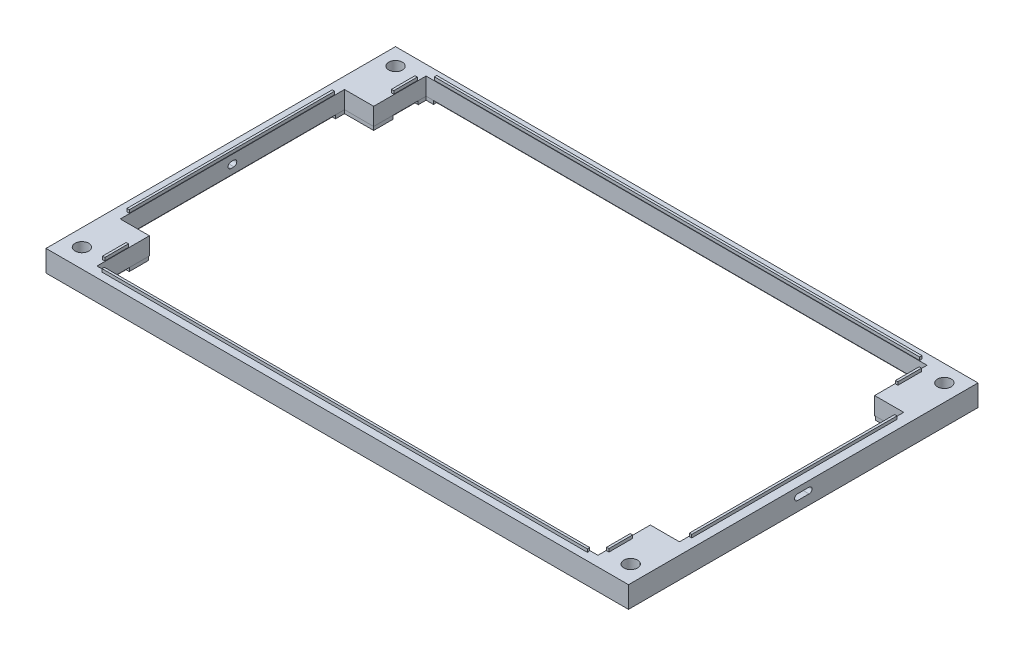
SolidWorks part; units mm, degrees
ref_plane "Front Plane" through (0, 0, 0) normal (0, 0, 1) x (1, 0, 0)
ref_plane "Top Plane" through (0, 0, 0) normal (0, 1, 0) x (1, 0, 0)
ref_plane "Right Plane" through (0, 0, 0) normal (1, 0, 0) x (0, 0, -1)
sketch "Sketch1" plane through (0, 0, 0) normal (0, 1, 0) x (1, 0, 0)
  line L0 (38.5216, 77.8504) -> (222.6228, 77.8504) construction
  line L1 (14, 116.5) -> (186, 116.5) construction
  line L2 (0, 120) -> (200, 120)
  line L3 (0, 120) -> (0, 0)
  line L4 (0, 0) -> (200, 0)
  line L5 (200, 120) -> (200, 0)
  line L6 (186, 116.5) -> (186, 98.5) construction
  line L7 (186, 98.5) -> (196, 98.5) construction
  line L8 (196, 98.5) -> (196, 21.5) construction
  line L9 (196, 21.5) -> (186, 21.5) construction
  line L10 (186, 21.5) -> (186, 3.5) construction
  line L11 (186, 3.5) -> (14, 3.5) construction
  line L12 (14, 3.5) -> (14, 21.5) construction
  line L13 (14, 21.5) -> (4, 21.5) construction
  line L14 (4, 21.5) -> (4, 98.5) construction
  line L15 (4, 98.5) -> (14, 98.5) construction
  line L16 (14, 98.5) -> (14, 116.5) construction
  line L17 (0, 60) -> (200, 60) construction
  line L18 (100, 120) -> (100, 0) construction
  line L19 (4, 60) -> (196, 60) construction
  line L20 (100, 116.5) -> (100, 3.5) construction
  line L21 (2.9, 20.4) -> (2.9, 99.6) construction
  line L22 (5.8062, 114.2159) -> (194.233, 114.2159) construction
  line L23 (5.8062, 114.2159) -> (5.8062, 6.516) construction
  line L24 (5.8062, 6.516) -> (194.233, 6.516) construction
  line L25 (194.233, 114.2159) -> (194.233, 6.516) construction
  line L26 (2.9, 99.6) -> (12.9, 99.6) construction
  line L27 (12.9, 99.6) -> (12.9, 117.6) construction
  line L28 (12.9, 117.6) -> (187.1, 117.6) construction
  line L29 (187.1, 117.6) -> (187.1, 99.6) construction
  line L30 (187.1, 99.6) -> (197.1, 99.6) construction
  line L31 (197.1, 99.6) -> (197.1, 20.4) construction
  line L32 (197.1, 20.4) -> (187.1, 20.4) construction
  line L33 (187.1, 20.4) -> (187.1, 2.4) construction
  line L34 (187.1, 2.4) -> (12.9, 2.4) construction
  line L35 (12.9, 2.4) -> (12.9, 20.4) construction
  line L36 (12.9, 20.4) -> (2.9, 20.4) construction
  line L85 (2.9, 95.4076) -> (4, 95.4076)
  line L86 (12.9, 105.4022) -> (14, 105.4022)
  line L87 (12.9, 113.8056) -> (14, 113.8056)
  line L88 (16.5433, 116.5) -> (16.5433, 117.6)
  line L89 (197.1, 95.4076) -> (196, 95.4076)
  line L90 (187.1, 105.4022) -> (186, 105.4022)
  line L91 (187.1, 113.8056) -> (186, 113.8056)
  line L92 (183.4567, 116.5) -> (183.4567, 117.6)
  line L93 (197.1, 24.5924) -> (196, 24.5924)
  line L94 (187.1, 14.5978) -> (186, 14.5978)
  line L95 (187.1, 6.1944) -> (186, 6.1944)
  line L96 (183.4567, 3.5) -> (183.4567, 2.4)
  line L97 (16.5433, 3.5) -> (16.5433, 2.4)
  line L98 (12.9, 6.1944) -> (14, 6.1944)
  line L99 (12.9, 14.5978) -> (14, 14.5978)
  line L100 (2.9, 24.5924) -> (4, 24.5924)
  line L101 (2.9, 95.4076) -> (2.9, 24.5924)
  line L102 (4, 24.5924) -> (4, 95.4076)
  line L103 (12.9, 14.5978) -> (12.9, 6.1944)
  line L104 (14, 6.1944) -> (14, 14.5978)
  line L105 (16.5433, 3.5) -> (183.4567, 3.5)
  line L106 (183.4567, 2.4) -> (16.5433, 2.4)
  line L107 (186, 6.1944) -> (186, 14.5978)
  line L108 (187.1, 14.5978) -> (187.1, 6.1944)
  line L109 (196, 24.5924) -> (196, 95.4076)
  line L110 (197.1, 95.4076) -> (197.1, 24.5924)
  line L111 (187.1, 105.4022) -> (187.1, 113.8056)
  line L112 (186, 113.8056) -> (186, 105.4022)
  line L113 (183.4567, 117.6) -> (16.5433, 117.6)
  line L114 (16.5433, 116.5) -> (183.4567, 116.5)
  line L115 (12.9, 105.4022) -> (12.9, 113.8056)
  line L116 (14, 113.8056) -> (14, 105.4022)
  line L117 (4, 95.4076) -> (4, 98.5)
  line L118 (4, 98.5) -> (14, 98.5)
  line L119 (14, 98.5) -> (14, 105.4022)
  line L120 (183.4567, 116.5) -> (186, 116.5)
  line L121 (186, 116.5) -> (186, 113.8056)
  line L122 (186, 105.4022) -> (186, 98.5)
  line L123 (186, 98.5) -> (196, 98.5)
  line L124 (196, 98.5) -> (196, 95.4076)
  line L125 (196, 24.5924) -> (196, 21.5)
  line L126 (196, 21.5) -> (186, 21.5)
  line L127 (186, 21.5) -> (186, 14.5978)
  line L128 (186, 6.1944) -> (186, 3.5)
  line L129 (186, 3.5) -> (183.4567, 3.5)
  line L130 (16.5433, 3.5) -> (14, 3.5)
  line L131 (14, 3.5) -> (14, 6.1944)
  line L132 (14, 14.5978) -> (14, 21.5)
  line L133 (14, 21.5) -> (4, 21.5)
  line L134 (4, 21.5) -> (4, 24.5924)
  line L135 (14, 113.8056) -> (14, 116.5)
  line L136 (14, 116.5) -> (16.5433, 116.5)
  circle A0 centre (5.8062, 114.2159) radius 2.35
  circle A1 centre (194.233, 114.2159) radius 2.35
  circle A2 centre (194.233, 6.516) radius 2.35
  circle A3 centre (5.8062, 6.516) radius 2.35
  dimension "D7" = 4.7
  dimension "D1" = 120
  dimension "D2" = 200
  dimension "D3" = 113
  dimension "D4" = 192
  dimension "D5" = 172
  dimension "D6" = 77
  dimension "D8" = 1.1
sketch "Sketch8" plane through (0, 0, 0) normal (0, 1, 0) x (1, 0, 0)
  line L0 (2.9, 24.5924) -> (4, 24.5924) construction
  line L1 (4, 21.5) -> (4, 24.5924) construction
  line L2 (14, 21.5) -> (4, 21.5) construction
  line L3 (14, 14.5978) -> (14, 21.5) construction
  line L4 (12.9, 14.5978) -> (14, 14.5978) construction
  line L5 (12.9, 14.5978) -> (12.9, 6.1944) construction
  line L6 (12.9, 6.1944) -> (14, 6.1944) construction
  line L7 (14, 3.5) -> (14, 6.1944) construction
  line L8 (16.5433, 3.5) -> (14, 3.5) construction
  line L9 (16.5433, 3.5) -> (16.5433, 2.4) construction
  line L10 (183.4567, 2.4) -> (16.5433, 2.4) construction
  line L11 (183.4567, 3.5) -> (183.4567, 2.4) construction
  line L12 (186, 3.5) -> (183.4567, 3.5) construction
  line L13 (186, 6.1944) -> (186, 3.5) construction
  line L14 (187.1, 6.1944) -> (186, 6.1944) construction
  line L15 (187.1, 14.5978) -> (187.1, 6.1944) construction
  line L16 (187.1, 14.5978) -> (186, 14.5978) construction
  line L17 (186, 21.5) -> (186, 14.5978) construction
  line L18 (196, 21.5) -> (186, 21.5) construction
  line L19 (196, 24.5924) -> (196, 21.5) construction
  line L20 (197.1, 24.5924) -> (196, 24.5924) construction
  line L21 (197.1, 95.4076) -> (197.1, 24.5924) construction
  line L22 (197.1, 95.4076) -> (196, 95.4076) construction
  line L23 (196, 98.5) -> (196, 95.4076) construction
  line L24 (186, 98.5) -> (196, 98.5) construction
  line L25 (186, 105.4022) -> (186, 98.5) construction
  line L26 (187.1, 105.4022) -> (186, 105.4022) construction
  line L27 (187.1, 105.4022) -> (187.1, 113.8056) construction
  line L28 (187.1, 113.8056) -> (186, 113.8056) construction
  line L29 (186, 116.5) -> (186, 113.8056) construction
  line L30 (183.4567, 116.5) -> (186, 116.5) construction
  line L31 (183.4567, 116.5) -> (183.4567, 117.6) construction
  line L32 (183.4567, 117.6) -> (16.5433, 117.6) construction
  line L33 (16.5433, 116.5) -> (16.5433, 117.6) construction
  line L34 (14, 116.5) -> (16.5433, 116.5) construction
  line L35 (14, 113.8056) -> (14, 116.5) construction
  line L36 (12.9, 113.8056) -> (14, 113.8056) construction
  line L37 (12.9, 105.4022) -> (12.9, 113.8056) construction
  line L38 (12.9, 105.4022) -> (14, 105.4022) construction
  line L39 (14, 98.5) -> (14, 105.4022) construction
  line L40 (4, 98.5) -> (14, 98.5) construction
  line L41 (4, 95.4076) -> (4, 98.5) construction
  line L42 (2.9, 95.4076) -> (4, 95.4076) construction
  line L43 (2.9, 95.4076) -> (2.9, 24.5924) construction
  line L44 (0, 0) -> (200, 0) construction
  line L45 (200, 120) -> (200, 0) construction
  line L46 (0, 120) -> (200, 120) construction
  line L47 (0, 120) -> (0, 0) construction
  line L48 (2.9, 24.5924) -> (4, 24.5924) construction
  line L49 (4, 21.5) -> (4, 24.5924) construction
  line L50 (14, 21.5) -> (4, 21.5) construction
  line L51 (14, 14.5978) -> (14, 21.5) construction
  line L52 (12.9, 14.5978) -> (14, 14.5978) construction
  line L53 (12.9, 14.5978) -> (12.9, 6.1944) construction
  line L54 (12.9, 6.1944) -> (14, 6.1944) construction
  line L55 (14, 3.5) -> (14, 6.1944) construction
  line L56 (16.5433, 3.5) -> (14, 3.5) construction
  line L57 (16.5433, 3.5) -> (16.5433, 2.4) construction
  line L58 (183.4567, 2.4) -> (16.5433, 2.4) construction
  line L59 (183.4567, 3.5) -> (183.4567, 2.4) construction
  line L60 (186, 3.5) -> (183.4567, 3.5) construction
  line L61 (186, 6.1944) -> (186, 3.5) construction
  line L62 (187.1, 6.1944) -> (186, 6.1944) construction
  line L63 (187.1, 14.5978) -> (187.1, 6.1944) construction
  line L64 (187.1, 14.5978) -> (186, 14.5978) construction
  line L65 (186, 21.5) -> (186, 14.5978) construction
  line L66 (196, 21.5) -> (186, 21.5) construction
  line L67 (196, 24.5924) -> (196, 21.5) construction
  line L68 (197.1, 24.5924) -> (196, 24.5924) construction
  line L69 (197.1, 95.4076) -> (197.1, 24.5924) construction
  line L70 (197.1, 95.4076) -> (196, 95.4076) construction
  line L71 (196, 98.5) -> (196, 95.4076) construction
  line L72 (186, 98.5) -> (196, 98.5) construction
  line L73 (186, 105.4022) -> (186, 98.5) construction
  line L74 (187.1, 105.4022) -> (186, 105.4022) construction
  line L75 (187.1, 105.4022) -> (187.1, 113.8056) construction
  line L76 (187.1, 113.8056) -> (186, 113.8056) construction
  line L77 (186, 116.5) -> (186, 113.8056) construction
  line L78 (183.4567, 116.5) -> (186, 116.5) construction
  line L79 (183.4567, 116.5) -> (183.4567, 117.6) construction
  line L80 (183.4567, 117.6) -> (16.5433, 117.6) construction
  line L81 (16.5433, 116.5) -> (16.5433, 117.6) construction
  line L82 (14, 116.5) -> (16.5433, 116.5) construction
  line L83 (14, 113.8056) -> (14, 116.5) construction
  line L84 (12.9, 113.8056) -> (14, 113.8056) construction
  line L85 (12.9, 105.4022) -> (12.9, 113.8056) construction
  line L86 (12.9, 105.4022) -> (14, 105.4022) construction
  line L87 (14, 98.5) -> (14, 105.4022) construction
  line L88 (4, 98.5) -> (14, 98.5) construction
  line L89 (4, 95.4076) -> (4, 98.5) construction
  line L90 (2.9, 95.4076) -> (4, 95.4076) construction
  line L91 (2.9, 95.4076) -> (2.9, 24.5924) construction
  line L92 (0, 0) -> (200, 0)
  line L93 (200, 120) -> (200, 0)
  line L94 (0, 120) -> (200, 120)
  line L95 (0, 120) -> (0, 0)
  line L96 (2.75, 95.5576) -> (2.75, 24.4424)
  line L97 (2.75, 24.4424) -> (3.85, 24.4424)
  line L98 (3.85, 21.35) -> (3.85, 24.4424)
  line L99 (13.85, 21.35) -> (3.85, 21.35)
  line L100 (13.85, 14.7478) -> (13.85, 21.35)
  line L101 (12.75, 14.7478) -> (13.85, 14.7478)
  line L102 (12.75, 14.7478) -> (12.75, 6.0444)
  line L103 (12.75, 6.0444) -> (13.85, 6.0444)
  line L104 (13.85, 3.35) -> (13.85, 6.0444)
  line L105 (16.3933, 3.35) -> (13.85, 3.35)
  line L106 (16.3933, 3.35) -> (16.3933, 2.25)
  line L107 (183.6067, 2.25) -> (16.3933, 2.25)
  line L108 (183.6067, 3.35) -> (183.6067, 2.25)
  line L109 (186.15, 3.35) -> (183.6067, 3.35)
  line L110 (186.15, 6.0444) -> (186.15, 3.35)
  line L111 (187.25, 6.0444) -> (186.15, 6.0444)
  line L112 (187.25, 14.7478) -> (187.25, 6.0444)
  line L113 (187.25, 14.7478) -> (186.15, 14.7478)
  line L114 (186.15, 21.35) -> (186.15, 14.7478)
  line L115 (196.15, 21.35) -> (186.15, 21.35)
  line L116 (196.15, 24.4424) -> (196.15, 21.35)
  line L117 (197.25, 24.4424) -> (196.15, 24.4424)
  line L118 (197.25, 95.5576) -> (197.25, 24.4424)
  line L119 (197.25, 95.5576) -> (196.15, 95.5576)
  line L120 (196.15, 98.65) -> (196.15, 95.5576)
  line L121 (186.15, 98.65) -> (196.15, 98.65)
  line L122 (186.15, 105.2522) -> (186.15, 98.65)
  line L123 (187.25, 105.2522) -> (186.15, 105.2522)
  line L124 (187.25, 105.2522) -> (187.25, 113.9556)
  line L125 (187.25, 113.9556) -> (186.15, 113.9556)
  line L126 (186.15, 116.65) -> (186.15, 113.9556)
  line L127 (183.6067, 116.65) -> (186.15, 116.65)
  line L128 (183.6067, 116.65) -> (183.6067, 117.75)
  line L129 (183.6067, 117.75) -> (16.3933, 117.75)
  line L130 (16.3933, 116.65) -> (16.3933, 117.75)
  line L131 (13.85, 116.65) -> (16.3933, 116.65)
  line L132 (13.85, 113.9556) -> (13.85, 116.65)
  line L133 (12.75, 113.9556) -> (13.85, 113.9556)
  line L134 (12.75, 105.2522) -> (12.75, 113.9556)
  line L135 (12.75, 105.2522) -> (13.85, 105.2522)
  line L136 (13.85, 98.65) -> (13.85, 105.2522)
  line L137 (3.85, 98.65) -> (13.85, 98.65)
  line L138 (3.85, 95.5576) -> (3.85, 98.65)
  line L139 (2.75, 95.5576) -> (3.85, 95.5576)
  circle A0 centre (5.8062, 6.516) radius 2.35 construction
  circle A1 centre (194.233, 6.516) radius 2.35 construction
  circle A2 centre (194.233, 114.2159) radius 2.35 construction
  circle A3 centre (5.8062, 114.2159) radius 2.35 construction
  circle A4 centre (5.8062, 6.516) radius 2.35
  circle A5 centre (194.233, 6.516) radius 2.35
  circle A6 centre (194.233, 114.2159) radius 2.35
  circle A7 centre (5.8062, 114.2159) radius 2.35
  dimension "D1" = 0.15
extrude "Boss-Extrude4" add sketch "Sketch8" along normal blind 1.35 contours L94 L95 L92 L93 A7 A6 A5 A4 L96 L139 L138 L137 L136 L135 L134 L133 L132 L131 L130 L129 L128 L127 L126 L125 L124 L123 L122 L121 L120 L119 L118 L117 L116 L115 L114 L113 L112 L111 L110 L109 L108 L107 L106 L105 L104 L103
sketch "Sketch9" plane through (0, 1.35, 0) normal (0, 1, 0) x (1, 0, 0)
  line L0 (183.4567, 116.5) -> (186, 116.5) construction
  line L1 (186, 116.5) -> (186, 113.8056) construction
  line L2 (186, 113.8056) -> (186, 105.4022) construction
  line L3 (186, 105.4022) -> (186, 98.5) construction
  line L4 (186, 98.5) -> (196, 98.5) construction
  line L5 (196, 98.5) -> (196, 95.4076) construction
  line L6 (196, 24.5924) -> (196, 95.4076) construction
  line L7 (196, 24.5924) -> (196, 21.5) construction
  line L8 (196, 21.5) -> (186, 21.5) construction
  line L9 (186, 21.5) -> (186, 14.5978) construction
  line L10 (186, 6.1944) -> (186, 14.5978) construction
  line L11 (186, 6.1944) -> (186, 3.5) construction
  line L12 (186, 3.5) -> (183.4567, 3.5) construction
  line L13 (16.5433, 3.5) -> (183.4567, 3.5) construction
  line L14 (16.5433, 3.5) -> (14, 3.5) construction
  line L15 (14, 3.5) -> (14, 6.1944) construction
  line L16 (14, 6.1944) -> (14, 14.5978) construction
  line L17 (14, 14.5978) -> (14, 21.5) construction
  line L18 (14, 21.5) -> (4, 21.5) construction
  line L19 (4, 21.5) -> (4, 24.5924) construction
  line L20 (4, 24.5924) -> (4, 95.4076) construction
  line L21 (4, 95.4076) -> (4, 98.5) construction
  line L22 (4, 98.5) -> (14, 98.5) construction
  line L23 (14, 98.5) -> (14, 105.4022) construction
  line L24 (14, 116.5) -> (16.5433, 116.5) construction
  line L25 (14, 113.8056) -> (14, 116.5) construction
  line L26 (14, 113.8056) -> (14, 105.4022) construction
  line L27 (16.5433, 116.5) -> (183.4567, 116.5) construction
  line L28 (0, 0) -> (200, 0) construction
  line L29 (200, 120) -> (200, 0) construction
  line L30 (0, 120) -> (200, 120) construction
  line L31 (0, 120) -> (0, 0) construction
  line L32 (183.4567, 116.5) -> (186, 116.5)
  line L33 (186, 116.5) -> (186, 113.8056)
  line L34 (186, 113.8056) -> (186, 105.4022)
  line L35 (186, 105.4022) -> (186, 98.5)
  line L36 (186, 98.5) -> (196, 98.5)
  line L37 (196, 98.5) -> (196, 95.4076)
  line L38 (196, 24.5924) -> (196, 95.4076)
  line L39 (196, 24.5924) -> (196, 21.5)
  line L40 (196, 21.5) -> (186, 21.5)
  line L41 (186, 21.5) -> (186, 14.5978)
  line L42 (186, 6.1944) -> (186, 14.5978)
  line L43 (186, 6.1944) -> (186, 3.5)
  line L44 (186, 3.5) -> (183.4567, 3.5)
  line L45 (16.5433, 3.5) -> (183.4567, 3.5)
  line L46 (16.5433, 3.5) -> (14, 3.5)
  line L47 (14, 3.5) -> (14, 6.1944)
  line L48 (14, 6.1944) -> (14, 14.5978)
  line L49 (14, 14.5978) -> (14, 21.5)
  line L50 (14, 21.5) -> (4, 21.5)
  line L51 (4, 21.5) -> (4, 24.5924)
  line L52 (4, 24.5924) -> (4, 95.4076)
  line L53 (4, 95.4076) -> (4, 98.5)
  line L54 (4, 98.5) -> (14, 98.5)
  line L55 (14, 98.5) -> (14, 105.4022)
  line L56 (14, 116.5) -> (16.5433, 116.5)
  line L57 (14, 113.8056) -> (14, 116.5)
  line L58 (14, 113.8056) -> (14, 105.4022)
  line L59 (16.5433, 116.5) -> (183.4567, 116.5)
  line L60 (0, 0) -> (200, 0)
  line L61 (200, 120) -> (200, 0)
  line L62 (0, 120) -> (200, 120)
  line L63 (0, 120) -> (0, 0)
  circle A0 centre (194.233, 114.2159) radius 2.35 construction
  circle A1 centre (194.233, 6.516) radius 2.35 construction
  circle A2 centre (5.8062, 6.516) radius 2.35 construction
  circle A3 centre (5.8062, 114.2159) radius 2.35 construction
  circle A4 centre (194.233, 114.2159) radius 2.35
  circle A5 centre (194.233, 6.516) radius 2.35
  circle A6 centre (5.8062, 6.516) radius 2.35
  circle A7 centre (5.8062, 114.2159) radius 2.35
extrude "Boss-Extrude5" add sketch "Sketch9" along normal blind 6
sketch "Sketch10" plane through (0, 7.35, 0) normal (0, 1, 0) x (1, 0, 0)
  line L0 (187.1, 113.8056) -> (186, 113.8056) construction
  line L1 (186, 113.8056) -> (186, 105.4022) construction
  line L2 (187.1, 105.4022) -> (187.1, 113.8056) construction
  line L3 (187.1, 105.4022) -> (186, 105.4022) construction
  line L12 (197.1, 95.4076) -> (196, 95.4076) construction
  line L13 (197.1, 95.4076) -> (197.1, 24.5924) construction
  line L14 (196, 24.5924) -> (196, 95.4076) construction
  line L15 (197.1, 24.5924) -> (196, 24.5924) construction
  line L16 (187.1, 14.5978) -> (186, 14.5978) construction
  line L17 (187.1, 14.5978) -> (187.1, 6.1944) construction
  line L18 (186, 6.1944) -> (186, 14.5978) construction
  line L19 (187.1, 6.1944) -> (186, 6.1944) construction
  line L20 (183.4567, 3.5) -> (183.4567, 2.4) construction
  line L21 (183.4567, 2.4) -> (16.5433, 2.4) construction
  line L22 (16.5433, 3.5) -> (183.4567, 3.5) construction
  line L23 (16.5433, 3.5) -> (16.5433, 2.4) construction
  line L24 (12.9, 6.1944) -> (14, 6.1944) construction
  line L25 (14, 6.1944) -> (14, 14.5978) construction
  line L26 (12.9, 14.5978) -> (12.9, 6.1944) construction
  line L27 (12.9, 14.5978) -> (14, 14.5978) construction
  line L28 (2.9, 24.5924) -> (4, 24.5924) construction
  line L29 (4, 24.5924) -> (4, 95.4076) construction
  line L30 (2.9, 95.4076) -> (2.9, 24.5924) construction
  line L31 (2.9, 95.4076) -> (4, 95.4076) construction
  line L32 (16.5433, 116.5) -> (183.4567, 116.5) construction
  line L33 (16.5433, 116.5) -> (16.5433, 117.6) construction
  line L34 (183.4567, 117.6) -> (16.5433, 117.6) construction
  line L35 (12.9, 105.4022) -> (14, 105.4022) construction
  line L36 (14, 113.8056) -> (14, 105.4022) construction
  line L37 (12.9, 105.4022) -> (12.9, 113.8056) construction
  line L38 (12.9, 113.8056) -> (14, 113.8056) construction
  line L39 (187.1, 113.8056) -> (186, 113.8056) construction
  line L40 (186, 113.8056) -> (186, 105.4022) construction
  line L41 (187.1, 105.4022) -> (187.1, 113.8056) construction
  line L42 (187.1, 105.4022) -> (186, 105.4022) construction
  line L43 (197.1, 95.4076) -> (196, 95.4076) construction
  line L44 (197.1, 95.4076) -> (197.1, 24.5924) construction
  line L45 (196, 24.5924) -> (196, 95.4076) construction
  line L46 (197.1, 24.5924) -> (196, 24.5924) construction
  line L47 (187.1, 14.5978) -> (186, 14.5978) construction
  line L48 (187.1, 14.5978) -> (187.1, 6.1944) construction
  line L49 (186, 6.1944) -> (186, 14.5978) construction
  line L50 (187.1, 6.1944) -> (186, 6.1944) construction
  line L51 (183.4567, 3.5) -> (183.4567, 2.4) construction
  line L52 (183.4567, 2.4) -> (16.5433, 2.4) construction
  line L53 (16.5433, 3.5) -> (183.4567, 3.5) construction
  line L54 (16.5433, 3.5) -> (16.5433, 2.4) construction
  line L55 (12.9, 6.1944) -> (14, 6.1944) construction
  line L56 (14, 6.1944) -> (14, 14.5978) construction
  line L57 (12.9, 14.5978) -> (12.9, 6.1944) construction
  line L58 (12.9, 14.5978) -> (14, 14.5978) construction
  line L59 (2.9, 24.5924) -> (4, 24.5924) construction
  line L60 (4, 24.5924) -> (4, 95.4076) construction
  line L61 (2.9, 95.4076) -> (2.9, 24.5924) construction
  line L62 (2.9, 95.4076) -> (4, 95.4076) construction
  line L63 (16.5433, 116.5) -> (183.4567, 116.5) construction
  line L64 (16.5433, 116.5) -> (16.5433, 117.6) construction
  line L65 (183.4567, 117.6) -> (16.5433, 117.6) construction
  line L66 (12.9, 105.4022) -> (14, 105.4022) construction
  line L67 (14, 113.8056) -> (14, 105.4022) construction
  line L68 (12.9, 105.4022) -> (12.9, 113.8056) construction
  line L69 (12.9, 113.8056) -> (14, 113.8056) construction
  line L70 (183.4567, 116.5) -> (183.4567, 117.6) construction
  line L71 (183.4567, 116.5) -> (183.4567, 117.6) construction
  line L72 (13.05, 105.5522) -> (13.85, 105.5522)
  line L73 (13.85, 113.6556) -> (13.85, 105.5522)
  line L74 (13.05, 113.6556) -> (13.85, 113.6556)
  line L75 (13.05, 105.5522) -> (13.05, 113.6556)
  line L76 (186.95, 113.6556) -> (186.15, 113.6556)
  line L77 (186.15, 113.6556) -> (186.15, 105.5522)
  line L78 (186.95, 105.5522) -> (186.15, 105.5522)
  line L79 (186.95, 105.5522) -> (186.95, 113.6556)
  line L80 (183.3067, 117.45) -> (16.6933, 117.45)
  line L81 (16.6933, 116.65) -> (16.6933, 117.45)
  line L82 (16.6933, 116.65) -> (183.3067, 116.65)
  line L83 (183.3067, 116.65) -> (183.3067, 117.45)
  line L84 (196.95, 95.2576) -> (196.15, 95.2576)
  line L85 (196.15, 24.7424) -> (196.15, 95.2576)
  line L86 (196.95, 24.7424) -> (196.15, 24.7424)
  line L87 (196.95, 95.2576) -> (196.95, 24.7424)
  line L88 (186.95, 14.4478) -> (186.15, 14.4478)
  line L89 (186.15, 6.3444) -> (186.15, 14.4478)
  line L90 (186.95, 6.3444) -> (186.15, 6.3444)
  line L91 (186.95, 14.4478) -> (186.95, 6.3444)
  line L92 (16.6933, 3.35) -> (183.3067, 3.35)
  line L93 (183.3067, 3.35) -> (183.3067, 2.55)
  line L94 (183.3067, 2.55) -> (16.6933, 2.55)
  line L95 (16.6933, 3.35) -> (16.6933, 2.55)
  line L96 (13.05, 6.3444) -> (13.85, 6.3444)
  line L97 (13.85, 6.3444) -> (13.85, 14.4478)
  line L98 (13.05, 14.4478) -> (13.85, 14.4478)
  line L99 (13.05, 14.4478) -> (13.05, 6.3444)
  line L100 (3.05, 24.7424) -> (3.85, 24.7424)
  line L101 (3.85, 24.7424) -> (3.85, 95.2576)
  line L102 (3.05, 95.2576) -> (3.85, 95.2576)
  line L103 (3.05, 95.2576) -> (3.05, 24.7424)
  dimension "D1" = 0.15
  dimension "D2" = 0.15
  dimension "D3" = 0.15
  dimension "D4" = 0.15
  dimension "D5" = 0.15
extrude "Boss-Extrude6" add sketch "Sketch10" along normal blind 1.05
sketch "Sketch11" plane through (0, 0, 0) normal (-1, 0, 0) x (0, 0, 1)
  line L0 (-95.5576, 1.35) -> (-24.4424, 1.35) construction
  line L1 (-95.5576, 1.35) -> (-24.4424, 1.35) construction
  line L2 (-60, 1.35) -> (-60, 7.35) construction
  line L3 (-60.5, 4.35) -> (-59.5, 4.35) construction
  line L4 (-120, 0) -> (0, 0)
  line L5 (0, 0) -> (0, 7.35)
  line L6 (0, 7.35) -> (-120, 7.35)
  line L7 (-120, 7.35) -> (-120, 0)
  line L8 (-120, 0) -> (0, 0)
  line L9 (0, 0) -> (0, 7.35)
  line L10 (0, 7.35) -> (-120, 7.35) construction
  line L11 (-120, 7.35) -> (-120, 0)
  line L12 (-60.5, 5.35) -> (-59.5, 5.35)
  line L13 (-60.5, 3.35) -> (-59.5, 3.35)
  line L14 (-61.5, 4.35) -> (-58.5, 4.35) construction
  arc A0 (-60.5, 5.35) -> (-60.5, 3.35) centre (-60.5, 4.35) ccw
  arc A1 (-59.5, 3.35) -> (-59.5, 5.35) centre (-59.5, 4.35) ccw
  point P10 (-60, 4.35)
  dimension "D2" = 2
  dimension "D3" = 3
  dimension "D1" = 0
extrude "Cut-Extrude1" cut sketch "Sketch11" against normal up to next contours L13 A1 L12 A0
sketch "Sketch12" plane through (200, 0, 0) normal (1, 0, 0) x (0, 0, -1)
  line L0 (95.5576, 1.35) -> (24.4424, 1.35) construction
  line L1 (24.7424, 7.35) -> (95.2576, 7.35) construction
  line L2 (95.5576, 1.35) -> (24.4424, 1.35) construction
  line L3 (24.7424, 7.35) -> (95.2576, 7.35) construction
  line L4 (60, 1.35) -> (60, 7.35) construction
  line L5 (58, 4.35) -> (62, 4.35) construction
  line L6 (58, 5.35) -> (62, 5.35)
  line L7 (58, 3.35) -> (62, 3.35)
  line L8 (57, 4.35) -> (63, 4.35) construction
  arc A0 (58, 5.35) -> (58, 3.35) centre (58, 4.35) ccw
  arc A1 (62, 3.35) -> (62, 5.35) centre (62, 4.35) ccw
  point P8 (60, 4.35)
  dimension "D1" = 2
  dimension "D2" = 6
extrude "Cut-Extrude2" cut sketch "Sketch12" against normal up to next
